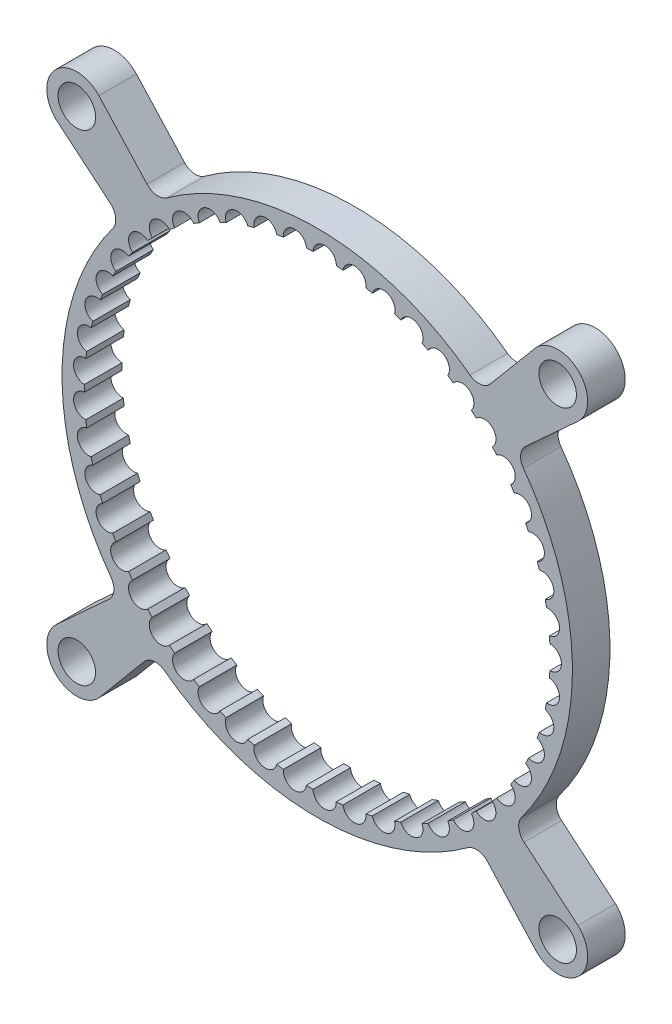
SolidWorks part; units mm, degrees
ref_plane "前视基准面" through (0, 0, 0) normal (0, 0, 1) x (1, 0, 0)
ref_plane "上视基准面" through (0, 0, 0) normal (0, 1, 0) x (1, 0, 0)
ref_plane "右视基准面" through (0, 0, 0) normal (1, 0, 0) x (0, 0, -1)
sketch "草图1" plane through (0, 0, 0) normal (0, 0, 1) x (1, 0, 0)
  line L0 (0, 0) -> (28.5, 0) construction
  line L1 (30.936, 2.4768) -> (30.9988, 1.4996) construction
  line L2 (30.9674, 1.9882) -> (32.4682, 2.0845) construction
  line L3 (30.936, -2.4768) -> (30.9988, -1.4996) construction
  line L4 (30.9674, -1.9882) -> (32.4682, -2.0845) construction
  line L5 (30.9674, -1.9882) -> (30.9956, -1.5491)
  line L6 (30.9674, 1.9882) -> (30.9962, 1.5394)
  line L7 (30.4589, -5.9319) -> (30.543, -5.5)
  line L8 (30.9674, -1.9882) -> (30.9386, -2.4369)
  line L9 (29.4503, -9.7782) -> (29.5889, -9.3606)
  line L10 (30.4589, -5.9319) -> (30.3729, -6.3732)
  line L11 (27.9581, -13.4639) -> (28.149, -13.0675)
  line L12 (29.4503, -9.7782) -> (29.3086, -10.2049)
  line L13 (26.0068, -16.9286) -> (26.2469, -16.5598)
  line L14 (27.9581, -13.4639) -> (27.763, -13.869)
  line L15 (23.6285, -20.1153) -> (23.9138, -19.7802)
  line L16 (26.0068, -16.9286) -> (25.7615, -17.3054)
  line L17 (20.8623, -22.9717) -> (21.188, -22.6759)
  line L18 (23.6285, -20.1153) -> (23.337, -20.4577)
  line L19 (17.7534, -25.4509) -> (18.1143, -25.1991)
  line L20 (20.8623, -22.9717) -> (20.5294, -23.274)
  line L21 (14.3531, -27.5122) -> (14.7432, -27.3087)
  line L22 (17.7534, -25.4509) -> (17.3846, -25.7081)
  line L23 (10.7171, -29.1217) -> (11.13, -28.9698)
  line L24 (14.3531, -27.5122) -> (13.9544, -27.7202)
  line L25 (6.9051, -30.2531) -> (7.334, -30.1552)
  line L26 (10.7171, -29.1217) -> (10.2951, -29.277)
  line L27 (2.9797, -30.8877) -> (3.4177, -30.8455)
  line L28 (6.9051, -30.2531) -> (6.4667, -30.3532)
  line L29 (-0.9946, -31.0152) -> (-0.5548, -31.0293)
  line L30 (2.9797, -30.8877) -> (2.5321, -30.9309)
  line L31 (-4.9526, -30.6334) -> (-4.5182, -30.7036)
  line L32 (-0.9946, -31.0152) -> (-1.444, -31.0008)
  line L33 (-8.8292, -29.7486) -> (-8.4074, -29.8737)
  line L34 (-4.9526, -30.6334) -> (-5.3965, -30.5616)
  line L35 (-12.5609, -28.3753) -> (-12.1585, -28.5534)
  line L36 (-8.8292, -29.7486) -> (-9.2603, -29.6206)
  line L37 (-16.0863, -26.5361) -> (-15.71, -26.7641)
  line L38 (-12.5609, -28.3753) -> (-12.9721, -28.1932)
  line L39 (-19.3476, -24.2611) -> (-19.0036, -24.5355)
  line L40 (-16.0863, -26.5361) -> (-16.4708, -26.3029)
  line L41 (-22.2912, -21.5878) -> (-21.9851, -21.9039)
  line L42 (-19.3476, -24.2611) -> (-19.6992, -23.9808)
  line L43 (-24.8688, -18.5601) -> (-24.6056, -18.9127)
  line L44 (-22.2912, -21.5878) -> (-22.604, -21.2648)
  line L45 (-27.038, -15.2275) -> (-26.8221, -15.6109)
  line L46 (-24.8688, -18.5601) -> (-25.1377, -18.1997)
  line L47 (-28.7633, -11.645) -> (-28.5982, -12.0528)
  line L48 (-27.038, -15.2275) -> (-27.2587, -14.8357)
  line L49 (-30.0163, -7.8712) -> (-29.9047, -8.2968)
  line L50 (-28.7633, -11.645) -> (-28.932, -11.2282)
  line L51 (-30.7764, -3.9682) -> (-30.7201, -4.4046)
  line L52 (-30.0163, -7.8712) -> (-30.1303, -7.4362)
  line L53 (-31.0311, 0) -> (-31.0311, -0.44)
  line L54 (-30.7764, -3.9682) -> (-30.8339, -3.5222)
  line L55 (-30.7764, 3.9682) -> (-30.8326, 3.5318)
  line L56 (-31.0311, 0) -> (-31.0311, 0.4497)
  line L57 (-30.0163, 7.8712) -> (-30.1279, 7.4456)
  line L58 (-30.7764, 3.9682) -> (-30.7189, 4.4142)
  line L59 (-28.7633, 11.645) -> (-28.9284, 11.2371)
  line L60 (-30.0163, 7.8712) -> (-29.9022, 8.3062)
  line L61 (-27.038, 15.2275) -> (-27.2539, 14.8441)
  line L62 (-28.7633, 11.645) -> (-28.5945, 12.0618)
  line L63 (-24.8688, 18.5601) -> (-25.1319, 18.2074)
  line L64 (-27.038, 15.2275) -> (-26.8173, 15.6193)
  line L65 (-22.2912, 21.5878) -> (-22.5973, 21.2717)
  line L66 (-24.8688, 18.5601) -> (-24.5998, 18.9204)
  line L67 (-19.3476, 24.2611) -> (-19.6916, 23.9868)
  line L68 (-22.2912, 21.5878) -> (-21.9784, 21.9108)
  line L69 (-16.0863, 26.5361) -> (-16.4626, 26.308)
  line L70 (-19.3476, 24.2611) -> (-18.996, 24.5415)
  line L71 (-12.5609, 28.3753) -> (-12.9632, 28.1972)
  line L72 (-16.0863, 26.5361) -> (-15.7018, 26.7692)
  line L73 (-8.8292, 29.7486) -> (-9.251, 29.6234)
  line L74 (-12.5609, 28.3753) -> (-12.1497, 28.5573)
  line L75 (-4.9526, 30.6334) -> (-5.3869, 30.5631)
  line L76 (-8.8292, 29.7486) -> (-8.3981, 29.8765)
  line L77 (-0.9946, 31.0152) -> (-1.4344, 31.0011)
  line L78 (-4.9526, 30.6334) -> (-4.5087, 30.7051)
  line L79 (2.9797, 30.8877) -> (2.5417, 30.93)
  line L80 (-0.9946, 31.0152) -> (-0.5452, 31.0296)
  line L81 (6.9051, 30.2531) -> (6.4761, 30.351)
  line L82 (2.9797, 30.8877) -> (3.4273, 30.8446)
  line L83 (10.7171, 29.1217) -> (10.3041, 29.2737)
  line L84 (6.9051, 30.2531) -> (7.3435, 30.1531)
  line L85 (14.3531, 27.5122) -> (13.963, 27.7157)
  line L86 (10.7171, 29.1217) -> (11.1391, 28.9664)
  line L87 (17.7534, 25.4509) -> (17.3926, 25.7026)
  line L88 (14.3531, 27.5122) -> (14.7518, 27.3042)
  line L89 (20.8623, 22.9717) -> (20.5365, 23.2675)
  line L90 (17.7534, 25.4509) -> (18.1222, 25.1936)
  line L91 (23.6285, 20.1153) -> (23.3433, 20.4503)
  line L92 (20.8623, 22.9717) -> (21.1951, 22.6694)
  line L93 (26.0068, 16.9286) -> (25.7668, 17.2973)
  line L94 (23.6285, 20.1153) -> (23.92, 19.7729)
  line L95 (27.9581, 13.4639) -> (27.7672, 13.8603)
  line L96 (26.0068, 16.9286) -> (26.2521, 16.5517)
  line L97 (29.4503, 9.7782) -> (29.3116, 10.1958)
  line L98 (27.9581, 13.4639) -> (28.1532, 13.0588)
  line L99 (30.4589, 5.9319) -> (30.3748, 6.3638)
  line L100 (29.4503, 9.7782) -> (29.592, 9.3514)
  line L101 (30.9674, 1.9882) -> (30.9392, 2.4273)
  line L102 (30.4589, 5.9319) -> (30.5449, 5.4905)
  line L103 (0, 0) -> (0, -28.5) construction
  line L104 (0, 0) -> (41.7841, -41.7841) construction
  line L105 (29.0849, -34.7363) -> (22.6815, -27.7408)
  line L106 (-34.7363, -29.0849) -> (-27.7408, -22.6815)
  line L109 (34.7363, -29.0849) -> (27.5593, -23.0756)
  line L112 (-29.0849, -34.7363) -> (-23.0756, -27.5593)
  line L115 (-29.0849, 34.7363) -> (-22.6815, 27.7408)
  line L121 (-34.7363, 29.0849) -> (-27.5593, 23.0756)
  line L122 (34.7363, 29.0849) -> (27.7408, 22.6815)
  line L123 (29.0849, 34.7363) -> (23.0756, 27.5593)
  circle A0 centre (0, 0) radius 34 construction
  circle A1 centre (0, 0) radius 32.535 construction
  circle A2 centre (31.035, 0) radius 1.5 construction
  circle A3 centre (30.7802, -3.9687) radius 1.5 construction
  circle A4 centre (30.02, -7.8722) radius 1.5 construction
  circle A5 centre (28.7669, -11.6464) radius 1.5 construction
  circle A6 centre (27.0414, -15.2294) radius 1.5 construction
  circle A7 centre (24.8719, -18.5624) radius 1.5 construction
  circle A8 centre (22.294, -21.5905) radius 1.5 construction
  circle A9 centre (19.35, -24.2641) radius 1.5 construction
  circle A10 centre (16.0883, -26.5394) radius 1.5 construction
  circle A11 centre (12.5625, -28.3788) radius 1.5 construction
  circle A12 centre (8.8303, -29.7523) radius 1.5 construction
  circle A13 centre (4.9532, -30.6372) radius 1.5 construction
  circle A14 centre (0.9947, -31.0191) radius 1.5 construction
  circle A15 centre (-2.9801, -30.8916) radius 1.5 construction
  circle A16 centre (-6.9059, -30.2569) radius 1.5 construction
  circle A17 centre (-10.7184, -29.1254) radius 1.5 construction
  circle A18 centre (-14.3549, -27.5156) radius 1.5 construction
  circle A19 centre (-17.7556, -25.454) radius 1.5 construction
  circle A20 centre (-20.8649, -22.9745) radius 1.5 construction
  circle A21 centre (-23.6315, -20.1178) radius 1.5 construction
  circle A22 centre (-26.0101, -16.9307) radius 1.5 construction
  circle A23 centre (-27.9616, -13.4656) radius 1.5 construction
  circle A24 centre (-29.4539, -9.7794) radius 1.5 construction
  circle A25 centre (-30.4627, -5.9326) radius 1.5 construction
  circle A26 centre (-30.9712, -1.9884) radius 1.5 construction
  circle A27 centre (-30.9712, 1.9884) radius 1.5 construction
  circle A28 centre (-30.4627, 5.9326) radius 1.5 construction
  circle A29 centre (-29.4539, 9.7794) radius 1.5 construction
  circle A30 centre (-27.9616, 13.4656) radius 1.5 construction
  circle A31 centre (-26.0101, 16.9307) radius 1.5 construction
  circle A32 centre (-23.6315, 20.1178) radius 1.5 construction
  circle A33 centre (-20.8649, 22.9745) radius 1.5 construction
  circle A34 centre (-17.7556, 25.454) radius 1.5 construction
  circle A35 centre (-14.3549, 27.5156) radius 1.5 construction
  circle A36 centre (-10.7184, 29.1254) radius 1.5 construction
  circle A37 centre (-6.9059, 30.2569) radius 1.5 construction
  circle A38 centre (-2.9801, 30.8916) radius 1.5 construction
  circle A39 centre (0.9947, 31.0191) radius 1.5 construction
  circle A40 centre (4.9532, 30.6372) radius 1.5 construction
  circle A41 centre (8.8303, 29.7523) radius 1.5 construction
  circle A42 centre (12.5625, 28.3788) radius 1.5 construction
  circle A43 centre (16.0883, 26.5394) radius 1.5 construction
  circle A44 centre (19.35, 24.2641) radius 1.5 construction
  circle A45 centre (22.294, 21.5905) radius 1.5 construction
  circle A46 centre (24.8719, 18.5624) radius 1.5 construction
  circle A47 centre (27.0414, 15.2294) radius 1.5 construction
  circle A48 centre (28.7669, 11.6464) radius 1.5 construction
  circle A49 centre (30.02, 7.8722) radius 1.5 construction
  circle A50 centre (30.7802, 3.9687) radius 1.5 construction
  circle A51 centre (0, 0) radius 31.035 construction
  arc A52 (30.9956, -1.5491) -> (32.535, 0) centre (30.9907, -0.0048) ccw
  arc A53 (30.9962, 1.5394) -> (32.535, 0) centre (30.9907, -0.0048) cw
  arc A54 (30.543, -5.5) -> (32.2679, -4.1605) centre (30.7357, -3.9678) ccw
  arc A55 (30.9386, -2.4369) -> (32.2679, -4.1605) centre (30.7357, -3.9678) cw
  arc A56 (29.5889, -9.3606) -> (31.4709, -8.2527) centre (29.976, -7.8656) ccw
  arc A57 (30.3729, -6.3732) -> (31.4709, -8.2527) centre (29.976, -7.8656) cw
  arc A58 (28.149, -13.0675) -> (30.1572, -12.2093) centre (28.724, -11.6343) ccw
  arc A59 (29.3086, -10.2049) -> (30.1572, -12.2093) centre (28.724, -11.6343) cw
  arc A60 (26.2469, -16.5598) -> (28.3484, -15.9655) centre (27.0005, -15.2119) ccw
  arc A61 (27.763, -13.869) -> (28.3484, -15.9655) centre (27.0005, -15.2119) cw
  arc A62 (23.9138, -19.7802) -> (26.074, -19.4595) centre (24.8335, -18.5398) ccw
  arc A63 (25.7615, -17.3054) -> (26.074, -19.4595) centre (24.8335, -18.5398) cw
  arc A64 (21.188, -22.6759) -> (23.3715, -22.634) centre (22.2588, -21.5632) ccw
  arc A65 (23.337, -20.4577) -> (23.3715, -22.634) centre (22.2588, -21.5632) cw
  arc A66 (18.1143, -25.1991) -> (20.2852, -25.4369) centre (19.3186, -24.2325) ccw
  arc A67 (20.5294, -23.274) -> (20.2852, -25.4369) centre (19.3186, -24.2325) cw
  arc A68 (14.7432, -27.3087) -> (16.8659, -27.8221) centre (16.0612, -26.504) ccw
  arc A69 (17.3846, -25.7081) -> (16.8659, -27.8221) centre (16.0612, -26.504) cw
  arc A70 (11.13, -28.9698) -> (13.1696, -29.7504) centre (12.5401, -28.3403) ccw
  arc A71 (13.9544, -27.7202) -> (13.1696, -29.7504) centre (12.5401, -28.3403) cw
  arc A72 (7.334, -30.1552) -> (9.2571, -31.1903) centre (8.8131, -29.7112) ccw
  arc A73 (10.2951, -29.277) -> (9.2571, -31.1903) centre (8.8131, -29.7112) cw
  arc A74 (3.4177, -30.8455) -> (5.1926, -32.118) centre (4.9414, -30.5943) ccw
  arc A75 (6.4667, -30.3532) -> (5.1926, -32.118) centre (4.9414, -30.5943) cw
  arc A76 (-0.5548, -31.0293) -> (1.0428, -32.5183) centre (0.9885, -30.975) ccw
  arc A77 (2.5321, -30.9309) -> (1.0428, -32.5183) centre (0.9885, -30.975) cw
  arc A78 (-4.5182, -30.7036) -> (-3.1241, -32.3847) centre (-2.9806, -30.8471) ccw
  arc A79 (-1.444, -31.0008) -> (-3.1241, -32.3847) centre (-2.9806, -30.8471) cw
  arc A80 (-8.4074, -29.8737) -> (-7.2397, -31.7193) centre (-6.9008, -30.2127) ccw
  arc A81 (-5.3965, -30.5616) -> (-7.2397, -31.7193) centre (-6.9008, -30.2127) cw
  arc A82 (-12.1585, -28.5534) -> (-11.2365, -30.5331) centre (-10.7076, -29.0822) ccw
  arc A83 (-9.2603, -29.6206) -> (-11.2365, -30.5331) centre (-10.7076, -29.0822) cw
  arc A84 (-15.71, -26.7641) -> (-15.0487, -28.8455) centre (-14.3387, -27.4741) ccw
  arc A85 (-12.9721, -28.1932) -> (-15.0487, -28.8455) centre (-14.3387, -27.4741) cw
  arc A86 (-19.0036, -24.5355) -> (-18.6138, -26.6843) centre (-17.7343, -25.415) ccw
  arc A87 (-16.4708, -26.3029) -> (-18.6138, -26.6843) centre (-17.7343, -25.415) cw
  arc A88 (-21.9851, -21.9039) -> (-21.8733, -24.0849) centre (-20.8387, -22.9385) ccw
  arc A89 (-19.6992, -23.9808) -> (-21.8733, -24.0849) centre (-20.8387, -22.9385) cw
  arc A90 (-24.6056, -18.9127) -> (-24.7736, -21.0901) centre (-23.6009, -20.0854) ccw
  arc A91 (-22.604, -21.2648) -> (-24.7736, -21.0901) centre (-23.6009, -20.0854) cw
  arc A92 (-26.8221, -15.6109) -> (-27.2672, -17.749) centre (-25.9756, -16.9025) ccw
  arc A93 (-25.1377, -18.1997) -> (-27.2672, -17.749) centre (-25.9756, -16.9025) cw
  arc A94 (-28.5982, -12.0528) -> (-29.313, -14.1164) centre (-27.9238, -13.442) ccw
  arc A95 (-27.2587, -14.8357) -> (-29.313, -14.1164) centre (-27.9238, -13.442) cw
  arc A96 (-29.9047, -8.2968) -> (-30.8775, -10.252) centre (-29.4135, -9.7609) ccw
  arc A97 (-28.932, -11.2282) -> (-30.8775, -10.252) centre (-29.4135, -9.7609) cw
  arc A98 (-30.7201, -4.4046) -> (-31.935, -6.2193) centre (-30.4202, -5.9194) ccw
  arc A99 (-30.1303, -7.4362) -> (-31.935, -6.2193) centre (-30.4202, -5.9194) cw
  arc A100 (-31.0311, -0.44) -> (-32.4682, -2.0845) centre (-30.9274, -1.9808) ccw
  arc A101 (-30.8339, -3.5222) -> (-32.4682, -2.0845) centre (-30.9274, -1.9808) cw
  arc A102 (-30.8326, 3.5318) -> (-32.4682, 2.0845) centre (-30.9268, 1.9904) ccw
  arc A103 (-31.0311, 0.4497) -> (-32.4682, 2.0845) centre (-30.9268, 1.9904) cw
  arc A104 (-30.1279, 7.4456) -> (-31.935, 6.2193) centre (-30.4183, 5.9289) ccw
  arc A105 (-30.7189, 4.4142) -> (-31.935, 6.2193) centre (-30.4183, 5.9289) cw
  arc A106 (-28.9284, 11.2371) -> (-30.8775, 10.252) centre (-29.4104, 9.77) ccw
  arc A107 (-29.9022, 8.3062) -> (-30.8775, 10.252) centre (-29.4104, 9.77) cw
  arc A108 (-27.2539, 14.8441) -> (-29.313, 14.1164) centre (-27.9196, 13.4507) ccw
  arc A109 (-28.5945, 12.0618) -> (-29.313, 14.1164) centre (-27.9196, 13.4507) cw
  arc A110 (-25.1319, 18.2074) -> (-27.2672, 17.749) centre (-25.9703, 16.9106) ccw
  arc A111 (-26.8173, 15.6193) -> (-27.2672, 17.749) centre (-25.9703, 16.9106) cw
  arc A112 (-22.5973, 21.2717) -> (-24.7736, 21.0901) centre (-23.5947, 20.0928) ccw
  arc A113 (-24.5998, 18.9204) -> (-24.7736, 21.0901) centre (-23.5947, 20.0928) cw
  arc A114 (-19.6916, 23.9868) -> (-21.8733, 24.0849) centre (-20.8315, 22.945) ccw
  arc A115 (-21.9784, 21.9108) -> (-21.8733, 24.0849) centre (-20.8315, 22.945) cw
  arc A116 (-16.4626, 26.308) -> (-18.6138, 26.6843) centre (-17.7264, 25.4205) ccw
  arc A117 (-18.996, 24.5415) -> (-18.6138, 26.6843) centre (-17.7264, 25.4205) cw
  arc A118 (-12.9632, 28.1972) -> (-15.0487, 28.8455) centre (-14.3301, 27.4786) ccw
  arc A119 (-15.7018, 26.7692) -> (-15.0487, 28.8455) centre (-14.3301, 27.4786) cw
  arc A120 (-9.251, 29.6234) -> (-11.2365, 30.5331) centre (-10.6986, 29.0855) ccw
  arc A121 (-12.1497, 28.5573) -> (-11.2365, 30.5331) centre (-10.6986, 29.0855) cw
  arc A122 (-5.3869, 30.5631) -> (-7.2397, 31.7193) centre (-6.8914, 30.2148) ccw
  arc A123 (-8.3981, 29.8765) -> (-7.2397, 31.7193) centre (-6.8914, 30.2148) cw
  arc A124 (-1.4344, 31.0011) -> (-3.1241, 32.3847) centre (-2.971, 30.848) ccw
  arc A125 (-4.5087, 30.7051) -> (-3.1241, 32.3847) centre (-2.971, 30.848) cw
  arc A126 (2.5417, 30.93) -> (1.0428, 32.5183) centre (0.9981, 30.9747) ccw
  arc A127 (-0.5452, 31.0296) -> (1.0428, 32.5183) centre (0.9981, 30.9747) cw
  arc A128 (6.4761, 30.351) -> (5.1926, 32.118) centre (4.9509, 30.5927) ccw
  arc A129 (3.4273, 30.8446) -> (5.1926, 32.118) centre (4.9509, 30.5927) cw
  arc A130 (10.3041, 29.2737) -> (9.2571, 31.1903) centre (8.8223, 29.7085) ccw
  arc A131 (7.3435, 30.1531) -> (9.2571, 31.1903) centre (8.8223, 29.7085) cw
  arc A132 (13.963, 27.7157) -> (13.1696, 29.7504) centre (12.5489, 28.3364) ccw
  arc A133 (11.1391, 28.9664) -> (13.1696, 29.7504) centre (12.5489, 28.3364) cw
  arc A134 (17.3926, 25.7026) -> (16.8659, 27.8221) centre (16.0695, 26.499) ccw
  arc A135 (14.7518, 27.3042) -> (16.8659, 27.8221) centre (16.0695, 26.499) cw
  arc A136 (20.5365, 23.2675) -> (20.2852, 25.4369) centre (19.3262, 24.2265) ccw
  arc A137 (18.1222, 25.1936) -> (20.2852, 25.4369) centre (19.3262, 24.2265) cw
  arc A138 (23.3433, 20.4503) -> (23.3715, 22.634) centre (22.2655, 21.5563) ccw
  arc A139 (21.1951, 22.6694) -> (23.3715, 22.634) centre (22.2655, 21.5563) cw
  arc A140 (25.7668, 17.2973) -> (26.074, 19.4595) centre (24.8393, 18.532) ccw
  arc A141 (23.92, 19.7729) -> (26.074, 19.4595) centre (24.8393, 18.532) cw
  arc A142 (27.7672, 13.8603) -> (28.3484, 15.9655) centre (27.0052, 15.2035) ccw
  arc A143 (26.2521, 16.5517) -> (28.3484, 15.9655) centre (27.0052, 15.2035) cw
  arc A144 (29.3116, 10.1958) -> (30.1572, 12.2093) centre (28.7277, 11.6253) ccw
  arc A145 (28.1532, 13.0588) -> (30.1572, 12.2093) centre (28.7277, 11.6253) cw
  arc A146 (30.3748, 6.3638) -> (31.4709, 8.2527) centre (29.9784, 7.8563) ccw
  arc A147 (29.592, 9.3514) -> (31.4709, 8.2527) centre (29.9784, 7.8563) cw
  arc A148 (30.9392, 2.4273) -> (32.2679, 4.1605) centre (30.7369, 3.9582) ccw
  arc A149 (30.5449, 5.4905) -> (32.2679, 4.1605) centre (30.7369, 3.9582) cw
  circle A201 centre (0, 0) radius 45.305 construction
  circle A202 centre (32.0355, -32.0355) radius 2.5
  circle A203 centre (32.0355, -32.0355) radius 4 construction
  arc A204 (29.0849, -34.7363) -> (34.7363, -29.0849) centre (32.0355, -32.0355) ccw
  arc A205 (-34.7363, -29.0849) -> (-29.0849, -34.7363) centre (-32.0355, -32.0355) ccw
  circle A206 centre (-32.0355, -32.0355) radius 2.5
  arc A207 (-29.0849, 34.7363) -> (-34.7363, 29.0849) centre (-32.0355, 32.0355) ccw
  circle A208 centre (-32.0355, 32.0355) radius 2.5
  arc A209 (34.7363, 29.0849) -> (29.0849, 34.7363) centre (32.0355, 32.0355) ccw
  circle A210 centre (32.0355, 32.0355) radius 2.5
  arc A211 (-20.3454, -27.2409) -> (20.0281, -27.475) centre (0, 0) ccw
  arc A212 (27.2409, -20.3454) -> (27.475, 20.0281) centre (0, 0) ccw
  arc A213 (20.3454, 27.2409) -> (-20.0281, 27.475) centre (0, 0) ccw
  arc A214 (-27.2409, 20.3454) -> (-27.475, -20.0281) centre (0, 0) ccw
  arc A215 (-23.0756, -27.5593) -> (-20.3454, -27.2409) centre (-21.5422, -28.8433) cw
  arc A216 (22.6815, -27.7408) -> (20.0281, -27.475) centre (21.2062, -29.0912) ccw
  arc A217 (27.5593, -23.0756) -> (27.2409, -20.3454) centre (28.8433, -21.5422) cw
  arc A218 (27.7408, 22.6815) -> (27.475, 20.0281) centre (29.0912, 21.2062) ccw
  arc A219 (23.0756, 27.5593) -> (20.3454, 27.2409) centre (21.5422, 28.8433) cw
  arc A220 (-22.6815, 27.7408) -> (-20.0281, 27.475) centre (-21.2062, 29.0912) ccw
  arc A221 (-27.5593, 23.0756) -> (-27.2409, 20.3454) centre (-28.8433, 21.5422) cw
  arc A222 (-27.7408, -22.6815) -> (-27.475, -20.0281) centre (-29.0912, -21.2062) ccw
  point P386 (21.4419, -26.3865)
  point P407 (26.0685, -21.8273)
  point P459 (-28.5, -28.5)
  dimension "D1" = 3
  dimension "D2" = 45
  dimension "D3" = 4
  dimension "D5" = 49
  dimension "D6" = 2
  dimension "D7" = 2
  dimension "D8" = 2
  dimension "D9" = 2
  dimension "D10" = 2
  dimension "D11" = 2
  dimension "D12" = 2
  dimension "D13" = 2
  dimension "D4" = 49
extrude "凸台-拉伸1" add sketch "草图1" along normal blind 5
